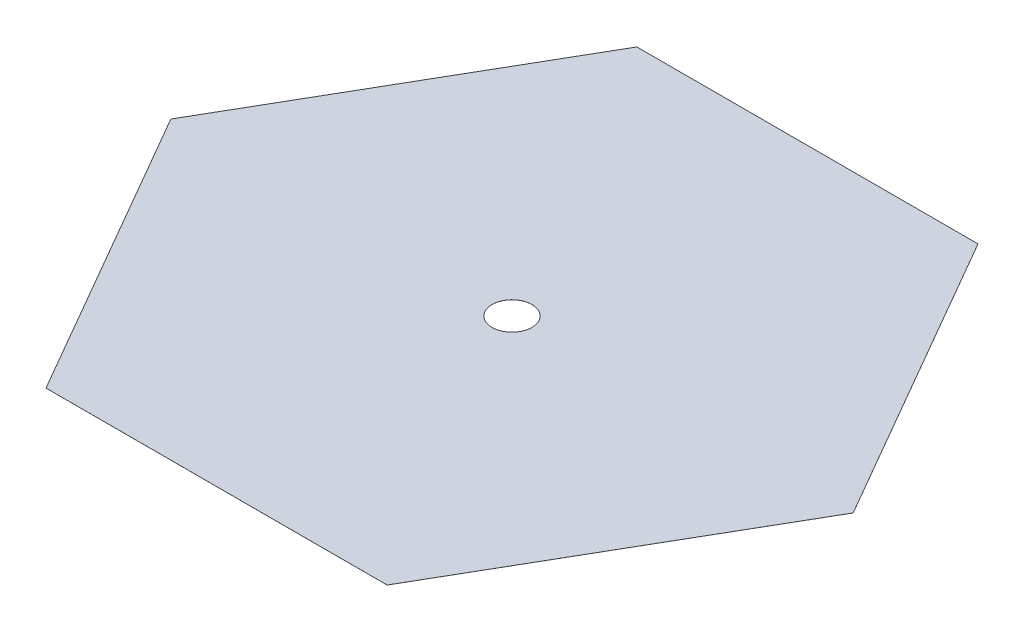
SolidWorks part; units mm, degrees
material "Ткань 600 кг/м3"
ref_plane "Спереди" through (0, 0, 0) normal (0, 0, 1) x (1, 0, 0)
ref_plane "Сверху" through (0, 0, 0) normal (0, 1, 0) x (1, 0, 0)
ref_plane "Справа" through (0, 0, 0) normal (1, 0, 0) x (0, 0, -1)
sketch "Эскиз1" plane through (0, 0, 0) normal (0, 1, 0) x (1, 0, 0)
  line L1 (-600, 0) -> (-300, -519.6152)
  line L2 (-300, -519.6152) -> (300, -519.6152)
  line L3 (300, -519.6152) -> (600, 0)
  line L4 (600, 0) -> (300, 519.6152)
  line L5 (300, 519.6152) -> (-300, 519.6152)
  line L6 (-300, 519.6152) -> (-600, 0)
  circle A0 centre (0, 0) radius 600 construction
  circle A1 centre (0, 0) radius 519.6152 construction
extrude "Бобышка-Вытянуть1" add sketch "Эскиз1" along normal blind 0.06
sketch "Эскиз2" plane through (0, 0.06, 0) normal (0, 1, 0) x (1, 0, 0)
  circle A0 centre (0, 0) radius 35
extrude "Вырез-Вытянуть1" cut sketch "Эскиз2" against normal blind 0.06
